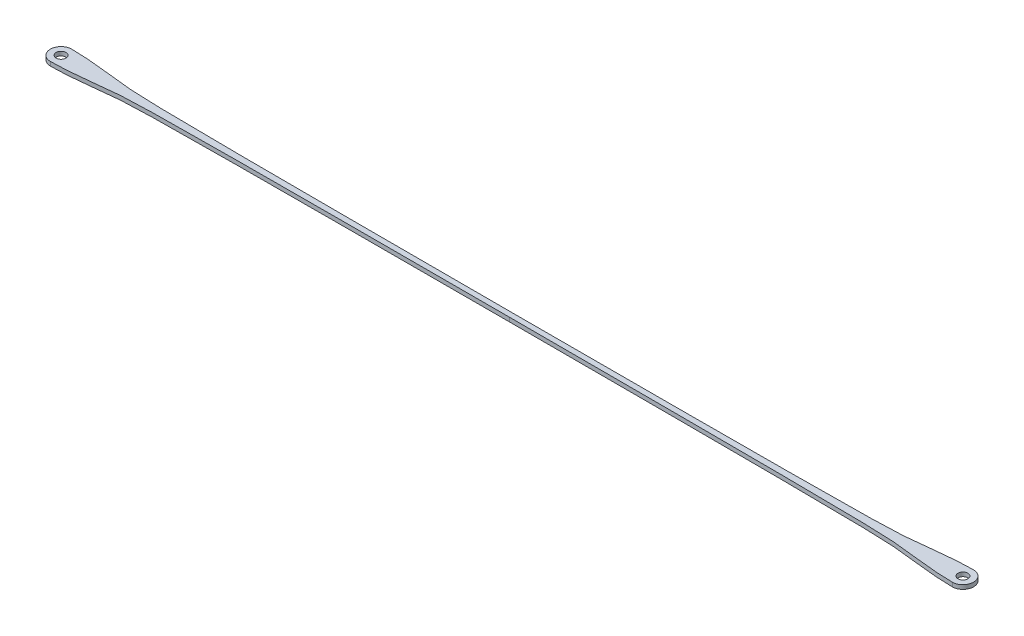
SolidWorks part; units mm, degrees
ref_plane "Front Plane" through (0, 0, 0) normal (0, 0, 1) x (1, 0, 0)
ref_plane "Top Plane" through (0, 0, 0) normal (0, 1, 0) x (1, 0, 0)
ref_plane "Right Plane" through (0, 0, 0) normal (1, 0, 0) x (0, 0, -1)
sketch "Sketch2" plane through (0, 0, 0) normal (0, 1, 0) x (1, 0, 0)
  line L1 (-55, 0) -> (55, 0) construction
  line L2 (55, 0.3191) -> (55, -0.3191)
  circle A0 centre (0, 0) radius 1.3
  spline S0 degree 3 poles (0, 1.3) (2.1583, 1.3) (7.5326, 0.5464) (11.2235, 0.3283) (55, 0.3191) knots 0 0 0 0 0.427834 1 1 1 1
  spline S1 degree 3 poles (0, -1.3) (2.1583, -1.3) (7.5326, -0.5464) (11.2235, -0.3283) (55, -0.3191) knots 0 0 0 0 0.427834 1 1 1 1
  dimension "D1" = 55
  dimension "D5" = 2.6
  dimension "D4" = 7.1253
  dimension "D6" = 15.0773
  dimension "D2" = 7.1943
  dimension "D3" = 1.364
  dimension "D7" = 0.6381
extrude "Boss-Extrude1" add sketch "Sketch2" along normal blind 0.5 contours A0 S1 L2 S0
sketch "Sketch3" plane through (0, 0.5, 0) normal (0, 1, 0) x (1, 0, 0)
  circle A0 centre (0, 0) radius 0.6
  dimension "D1" = 1.2
extrude "Cut-Extrude1" cut sketch "Sketch3" against normal blind 1
ref_plane "Plane1" through (55, 0, 0) normal (1, 0, 0) x (0, 0, -1)
mirror "Mirror1" about plane through (55, 0, 0) normal (1, 0, 0) of "Boss-Extrude1", "Cut-Extrude1"
